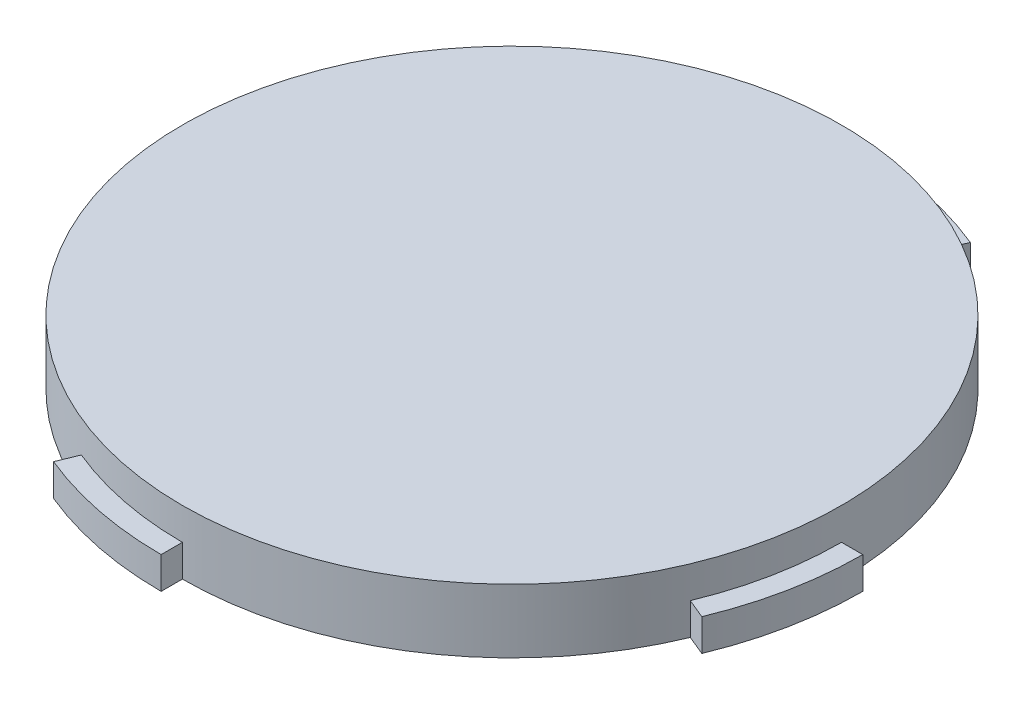
SolidWorks part; units mm, degrees
ref_plane "Front Plane" through (0, 0, 0) normal (0, 0, 1) x (1, 0, 0)
ref_plane "Top Plane" through (0, 0, 0) normal (0, 1, 0) x (1, 0, 0)
ref_plane "Right Plane" through (0, 0, 0) normal (1, 0, 0) x (0, 0, -1)
sketch "Sketch8" plane through (0, 0, 0) normal (0, 1, 0) x (1, 0, 0)
  line L0 (0, 33) -> (0, 31)
  line L1 (-33, 0) -> (-31, 0)
  line L10 (-12.6286, -30.488) -> (-11.8632, -28.6403)
  line L11 (-30.488, 12.6286) -> (-28.6403, 11.8632)
  line L13 (28.6403, -11.8632) -> (30.488, -12.6286)
  line L14 (31, 0) -> (33, 0)
  line L15 (0, -31) -> (0, -33)
  line L16 (11.8632, 28.6403) -> (12.6286, 30.488)
  circle A0 centre (0, 0) radius 31
  arc A1 (12.6286, 30.488) -> (0, 33) centre (0, 0) ccw
  arc A2 (-30.488, 12.6286) -> (-33, 0) centre (0, 0) ccw
  arc A3 (-12.6286, -30.488) -> (0, -33) centre (0, 0) ccw
  arc A4 (30.488, -12.6286) -> (33, 0) centre (0, 0) ccw
extrude "Boss-Extrude9" add sketch "Sketch8" along normal blind 3 contours A0 | L10 A3 L15 A0 | L11 A2 L1 A0 | L16 A1 L0 A0 | L13 A4 L14 A0
sketch "Sketch11" plane through (0, 3, 0) normal (0, 1, 0) x (1, 0, 0)
  circle A0 centre (0, 0) radius 31
extrude "Boss-Extrude10" add sketch "Sketch11" along normal blind 3
